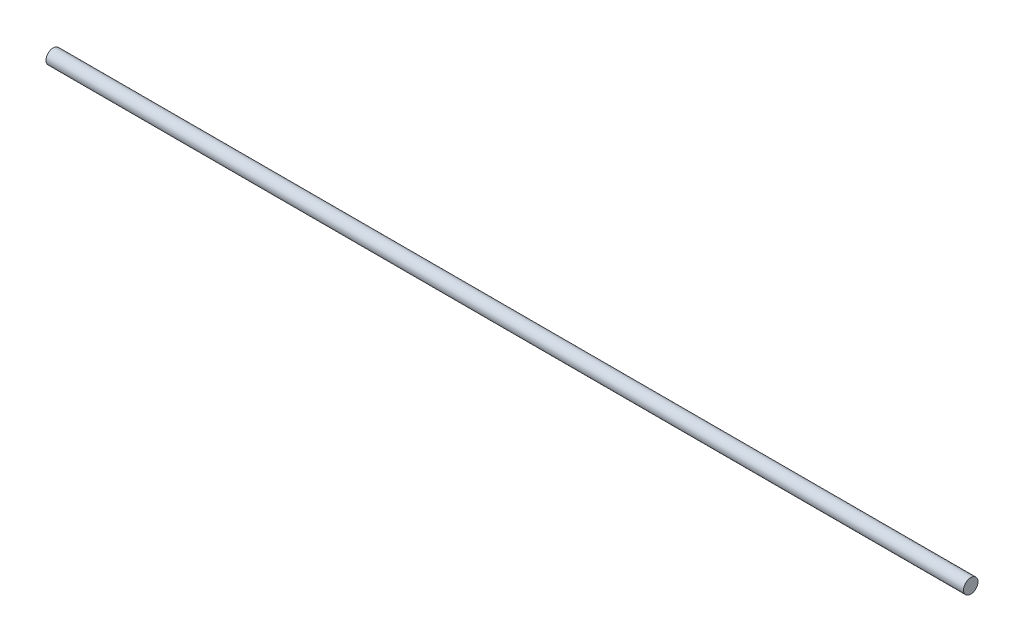
SolidWorks part; units mm, degrees
ref_plane "Alzado" through (0, 0, 0) normal (0, 0, 1) x (1, 0, 0)
ref_plane "Planta" through (0, 0, 0) normal (0, 1, 0) x (1, 0, 0)
ref_plane "Vista lateral" through (0, 0, 0) normal (1, 0, 0) x (0, 0, -1)
sketch "Croquis1" plane through (0, 0, 0) normal (1, 0, 0) x (0, 0, -1)
  circle A0 centre (0, 0) radius 2.5
extrude "Saliente-Extruir1" add sketch "Croquis1" along normal mid plane 317.53
